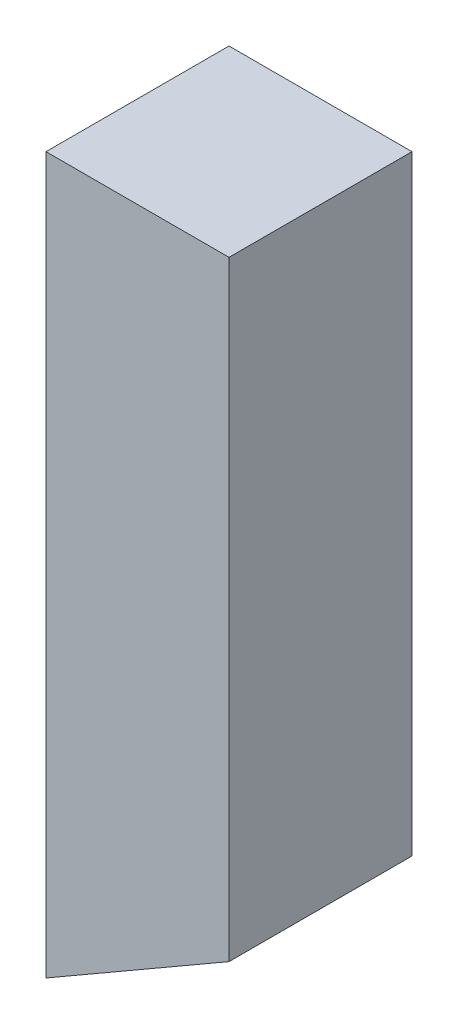
SolidWorks part; units mm, degrees
ref_plane "Plan de face" through (0, 0, 0) normal (0, 0, 1) x (1, 0, 0)
ref_plane "Plan de dessus" through (0, 0, 0) normal (0, 1, 0) x (1, 0, 0)
ref_plane "Plan de droite" through (0, 0, 0) normal (1, 0, 0) x (0, 0, -1)
sketch "Esquisse1" plane through (0, 0, 0) normal (0, 0, 1) x (1, 0, 0)
  line L1 (0, 0) -> (60, 0)
  line L2 (0, 0) -> (0, 200)
  line L3 (0, 200) -> (60, 200)
  line L4 (60, 0) -> (60, 200)
  dimension "D1" = 200
  dimension "D2" = 60
extrude "Boss.-Extru.1" add sketch "Esquisse1" along normal blind 60
sketch "Esquisse2" plane through (0, 0, 60) normal (0, 0, 1) x (1, 0, 0)
  line L0 (60, 0) -> (0, 0)
  line L1 (0, 0) -> (0, -34.641)
  line L2 (0, -34.641) -> (60, 0)
  dimension "D1" = 30
extrude "Boss.-Extru.2" add sketch "Esquisse2" against normal up to vertex (60 mm away) up to point (0, 0, 0)
